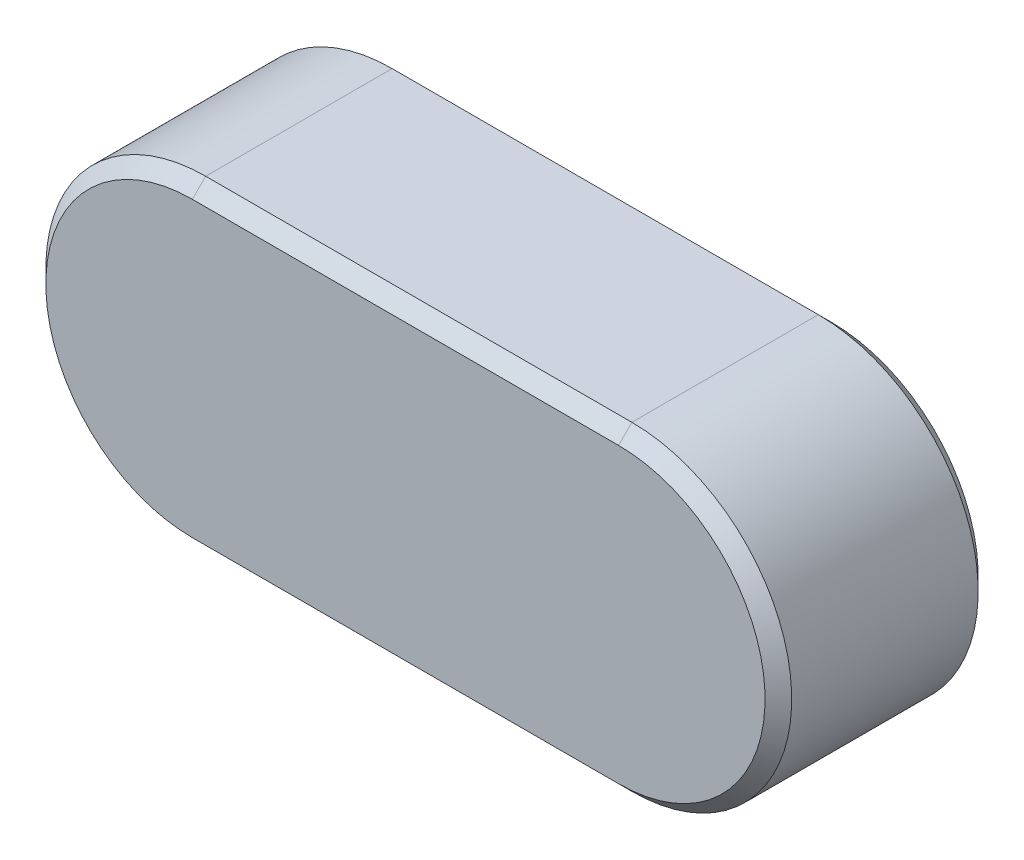
SolidWorks part; units mm, degrees
ref_plane "Front" through (0, 0, 0) normal (0, 0, 1) x (1, 0, 0)
ref_plane "Top" through (0, 0, 0) normal (0, 1, 0) x (1, 0, 0)
ref_plane "Right" through (0, 0, 0) normal (1, 0, 0) x (0, 0, -1)
sketch "Sketch1" plane through (0, 0, 0) normal (0, 0, 1) x (1, 0, 0)
  line L0 (0, 3) -> (-8, 3)
  line L1 (-8, -3) -> (0, -3)
  arc A0 (-8, 3) -> (-8, -3) centre (-8, 0) ccw
  arc A1 (0, -3) -> (0, 3) centre (0, 0) ccw
  dimension "b" = 6
  dimension "l" = 14
extrude "Extrude1" add sketch "Sketch1" along normal blind 4
sketch "Sketch2" plane through (0, 0, 0) normal (0, 0, 1) x (1, 0, 0)
  line L0 (0, 3) -> (-8, 3) construction
  line L1 (-11, 3) -> (3, 3)
  line L2 (-11, 3) -> (-11, -3)
  line L3 (-11, -3) -> (3, -3)
  line L4 (3, 3) -> (3, -3)
  line L5 (-8, -3) -> (0, -3) construction
  arc A0 (-8, 3) -> (-8, -3) centre (-8, 0) ccw construction
  arc A1 (0, -3) -> (0, 3) centre (0, 0) ccw construction
extrude "Extrude2" [suppressed] add sketch "Sketch2" along normal blind 4
sketch "Sketch3" plane through (0, 0, 0) normal (0, 0, 1) x (1, 0, 0)
  line L0 (-8, -3) -> (0, -3) construction
  line L1 (-8, -3) -> (3, -3)
  line L3 (-8, 3) -> (3, 3)
  line L4 (3, -3) -> (3, 3)
  arc A1 (-8, 3) -> (-8, -3) centre (-8, 0) ccw
  arc A2 (0, -3) -> (0, 3) centre (0, 0) ccw construction
  arc A3 (-8, 3) -> (-8, -3) centre (-8, 0) ccw construction
extrude "Extrude3" [suppressed] add sketch "Sketch3" along normal blind 4
chamfer "Chamfer1" distance 0.25 angle 45 8 edges at (-4, 3, 0) (-4, -3, 0) (-4, 3, 4) (-4, -3, 4) (-11, 0, 0) (-11, 0, 4) (3, 0, 0) (3, 0, 4)
equation "\"D1@Extrude2\" = \"h@Extrude1\""
equation "\"D1@Extrude3\" = \"h@Extrude1\""
